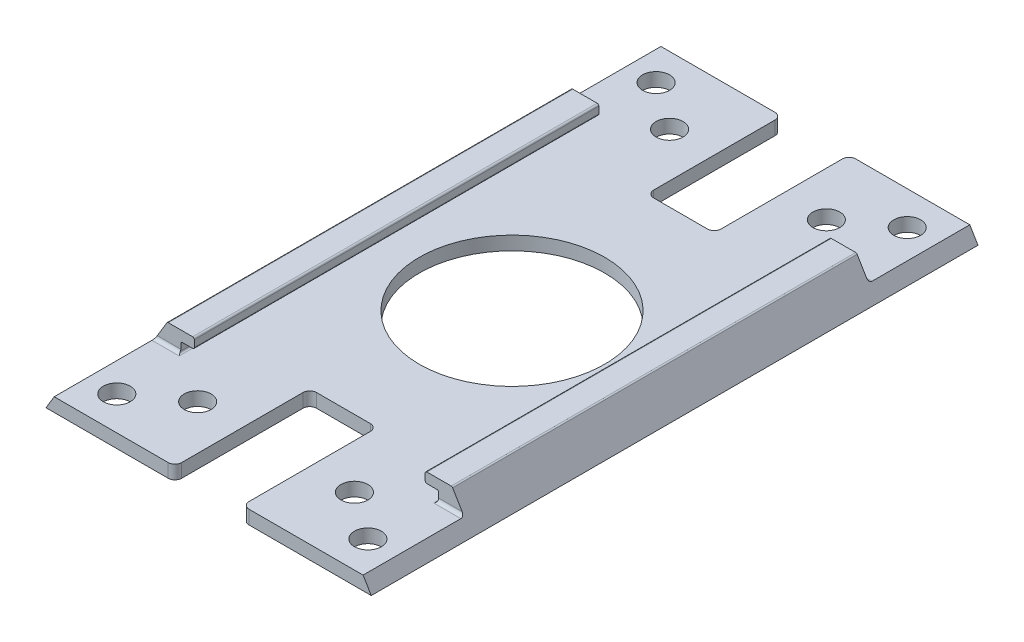
SolidWorks part; units mm, degrees
ref_plane "Front Plane" through (0, 0, 0) normal (0, 0, 1) x (1, 0, 0)
ref_plane "Top Plane" through (0, 0, 0) normal (0, 1, 0) x (1, 0, 0)
ref_plane "Right Plane" through (0, 0, 0) normal (1, 0, 0) x (0, 0, -1)
sketch "Sketch1" plane through (0, 0, 0) normal (0, 0, 1) x (1, 0, 0)
  line L0 (-79.85, -4.05) -> (3.65, -4.05)
  line L1 (0, 0) -> (-76.2, 0) construction
  line L2 (-76.2, 0) -> (-76.2, 2.8) construction
  line L3 (-76.35, 2.45) -> (-76.35, 0.5)
  line L4 (-76.2, 2.8) -> (-76.35, 2.8) construction
  line L5 (-76.2, 2.8) -> (-76.2, 2.95) construction
  line L6 (-76.2, 2.95) -> (-76.35, 2.95) construction
  line L7 (-76.35, 2.8) -> (-76.35, 2.95) construction
  line L8 (-75.85, 2.95) -> (-72.85, 2.95)
  line L9 (-72.35, 3.45) -> (-72.35, 5.45)
  line L10 (-72.85, 5.95) -> (-79.85, 5.95)
  line L13 (-38.1, -9.7056) -> (-38.1, 9.7056) construction
  line L16 (-79.85, 5.95) -> (-80.0669, 5.95)
  line L17 (-80.35, 5.95) -> (-80.35, -4.05) construction
  line L18 (-80.35, -4.05) -> (-86.35, -4.05)
  line L19 (-86.35, -4.05) -> (-80.4957, 5.7072)
  line L20 (-79.85, -4.05) -> (-80.35, -4.05)
  line L21 (-0.35, 0) -> (-75.85, 0)
  line L26 (4.15, 5.95) -> (4.15, -4.05) construction
  line L35 (0.15, 2.8) -> (0.15, 2.95) construction
  line L36 (0, 2.95) -> (0.15, 2.95) construction
  line L37 (0, 2.8) -> (0, 2.95) construction
  line L38 (0, 2.8) -> (0.15, 2.8) construction
  line L39 (0, 0) -> (0, 2.8) construction
  line L40 (3.65, -4.05) -> (4.15, -4.05)
  line L41 (10.15, -4.05) -> (4.2957, 5.7072)
  line L42 (4.15, -4.05) -> (10.15, -4.05)
  line L43 (3.65, 5.95) -> (3.8669, 5.95)
  line L44 (-3.35, 5.95) -> (3.65, 5.95)
  line L45 (-3.85, 3.45) -> (-3.85, 5.45)
  line L46 (-0.35, 2.95) -> (-3.35, 2.95)
  line L47 (0.15, 2.45) -> (0.15, 0.5)
  arc A0 (-72.35, 5.45) -> (-72.85, 5.95) centre (-72.85, 5.45) ccw
  arc A2 (-72.85, 2.95) -> (-72.35, 3.45) centre (-72.85, 3.45) ccw
  arc A4 (-76.35, 2.45) -> (-75.85, 2.95) centre (-75.85, 2.45) cw
  arc A5 (-76.35, 0.5) -> (-75.85, 0) centre (-75.85, 0.5) ccw
  arc A6 (-80.0669, 5.95) -> (-80.4957, 5.7072) centre (-80.0669, 5.45) ccw
  arc A12 (3.8669, 5.95) -> (4.2957, 5.7072) centre (3.8669, 5.45) cw
  arc A13 (0.15, 0.5) -> (-0.35, 0) centre (-0.35, 0.5) cw
  arc A14 (0.15, 2.45) -> (-0.35, 2.95) centre (-0.35, 2.45) ccw
  arc A15 (-3.35, 2.95) -> (-3.85, 3.45) centre (-3.35, 3.45) cw
  arc A16 (-3.85, 5.45) -> (-3.35, 5.95) centre (-3.35, 5.45) cw
  point P16 (-38.1, 0)
  point P21 (-72.35, 5.95)
  point P24 (-80.35, -4.05)
  point P27 (-72.35, 2.95)
  point P30 (-80.35, 5.95)
  point P60 (4.15, 5.95)
  point P61 (-3.85, 2.95)
  point P62 (4.15, -4.05)
  point P63 (-3.85, 5.95)
  dimension "D10" = 0.5
  dimension "D11" = 6
  dimension "D12" = 0.5
  dimension "D13" = 0.5
  dimension "D14" = 0.5
  dimension "D1" = 76.2
  dimension "D2" = 2.8
  dimension "D4" = 0.15
  dimension "D5" = 0.15
  dimension "D6" = 4
  dimension "D7" = 8
  dimension "D8" = 10
  dimension "D9" = 3
extrude "Boss-Extrude1" add sketch "Sketch1" along normal blind 180
sketch "Sketch2" plane through (0, 0, 180) normal (0, 0, 1) x (1, 0, 0)
  line L0 (-83.92, 0) -> (7.72, 0)
  line L1 (-86.35, -4.05) -> (-80.4957, 5.7072) construction
  line L2 (10.15, -4.05) -> (4.2957, 5.7072) construction
  line L3 (7.72, 0) -> (7.72, 8.017)
  line L4 (7.72, 8.017) -> (-83.92, 8.017)
  line L5 (-83.92, 8.017) -> (-83.92, 0)
  point P0 (7.72, 8.017)
  point P3 (-38.1, 0)
extrude "Cut-Extrude1" cut sketch "Sketch2" against normal blind 30
sketch "Sketch3" plane through (0, 0, 0) normal (0, 0, -1) x (-1, 0, 0)
  line L0 (83.92, 0) -> (-7.72, 0)
  line L1 (-7.72, 0) -> (-7.72, 8.4837)
  line L2 (-7.72, 8.4837) -> (83.92, 8.4837)
  line L3 (83.92, 8.4837) -> (83.92, 0)
  point P3 (38.1, 0)
  point P6 (0, 0)
  point P8 (0, 0)
  point P9 (0, 0)
  point P10 (0, 0)
  point P11 (-7.72, 0)
  point P13 (83.92, 0)
extrude "Cut-Extrude2" cut sketch "Sketch3" against normal blind 30
sketch "Sketch4" plane through (0, 0, 0) normal (0, 1, 0) x (1, 0, 0)
  line L0 (-178.1709, -90) -> (-35.3081, -90) construction
  line L1 (-38.1, -16.526) -> (-38.1, 16.526) construction
  line L2 (-86.35, 0) -> (-61.35, 0) construction
  line L4 (-61.35, 0) -> (-61.35, -20) construction
  line L5 (-61.35, -20) -> (-61.35, -10) construction
  line L6 (-61.35, -10) -> (-75.35, -10) construction
  line L7 (-14.85, 0) -> (-14.85, -20) construction
  line L8 (10.15, 0) -> (-14.85, 0) construction
  line L9 (-14.85, -10) -> (-0.85, -10) construction
  line L10 (-14.85, -20) -> (-14.85, -10) construction
  line L13 (-50.1, 0) -> (-86.35, 0)
  line L14 (-26.1, 0) -> (10.15, 0)
  line L15 (-50.1, 0) -> (-26.1, 0)
  line L16 (-14.85, -160) -> (-14.85, -170) construction
  line L17 (-14.85, -170) -> (-0.85, -170) construction
  line L18 (10.15, -180) -> (-14.85, -180) construction
  line L20 (10.15, -180) -> (10.15, 0) construction
  line L24 (-14.85, -180) -> (-14.85, -160) construction
  line L25 (-61.35, -170) -> (-75.35, -170) construction
  line L28 (-48.1, -2) -> (-48.1, -38)
  line L29 (-46.1, -40) -> (-30.1, -40)
  line L30 (-28.1, -38) -> (-28.1, -2)
  line L31 (-61.35, -160) -> (-61.35, -170) construction
  line L32 (-61.35, -180) -> (-61.35, -160) construction
  line L34 (-86.35, -180) -> (-61.35, -180) construction
  line L35 (-28.1, -142) -> (-28.1, -178)
  line L36 (-46.1, -140) -> (-30.1, -140)
  line L37 (-48.1, -178) -> (-48.1, -142)
  line L38 (-50.1, -180) -> (-26.1, -180)
  line L39 (-26.1, -180) -> (10.15, -180)
  line L40 (-50.1, -180) -> (-86.35, -180)
  line L41 (-86.35, -180) -> (-86.35, 0) construction
  circle A0 centre (-61.35, -20) radius 4
  circle A1 centre (-75.35, -10) radius 4
  circle A2 centre (-0.85, -10) radius 4
  circle A3 centre (-14.85, -20) radius 4
  circle A8 centre (-38.1, -90) radius 27.5
  arc A15 (-30.1, -40) -> (-28.1, -38) centre (-30.1, -38) ccw
  arc A16 (-48.1, -38) -> (-46.1, -40) centre (-46.1, -38) ccw
  arc A17 (-48.1, -2) -> (-50.1, 0) centre (-50.1, -2) ccw
  arc A18 (-28.1, -2) -> (-26.1, 0) centre (-26.1, -2) cw
  arc A19 (-28.1, -178) -> (-26.1, -180) centre (-26.1, -178) ccw
  arc A20 (-48.1, -178) -> (-50.1, -180) centre (-50.1, -178) cw
  arc A21 (-48.1, -142) -> (-46.1, -140) centre (-46.1, -142) cw
  arc A22 (-30.1, -140) -> (-28.1, -142) centre (-30.1, -142) cw
  circle A27 centre (-14.85, -160) radius 4
  circle A28 centre (-0.85, -170) radius 4
  circle A29 centre (-75.35, -170) radius 4
  circle A30 centre (-61.35, -160) radius 4
  point P3 (-38.1, -90)
  point P6 (-38.1, -90)
  point P27 (-38.1, 0)
  point P32 (-48.1, 0)
  point P36 (-28.1, 0)
  point P71 (-28.1, -180)
  point P72 (-48.1, -180)
  point P73 (-38.1, -180)
  point P74 (0, 0)
  point P75 (0, 0)
  point P76 (0, 0)
  point P77 (0, 0)
  point P78 (0, 0)
  point P79 (0, 0)
  dimension "D1" = 25
  dimension "D3" = 8
  dimension "D6" = 8
  dimension "D7" = 55
  dimension "D8" = 10
  dimension "D9" = 10
  dimension "D10" = 48.25
  dimension "D13" = 2
  dimension "D15" = 2
  dimension "D12" = 2
  dimension "D2" = 20
  dimension "D4" = 10
  dimension "D5" = 14
  dimension "D11" = 90
fillet "Fillet1" radius 1 1 edges at (-79.885, 0, 150)
fillet "Fillet2" radius 1 1 edges at (3.685, 0, 150)
fillet "Fillet3" radius 1 2 edges at (-79.885, 0, 30) (3.685, 0, 30)
extrude "Cut-Extrude3" cut sketch "Sketch4" against normal through all both contours L30 A18 L15 A17 L28 A16 L29 A15 | A1 | A0 | A3 | A2 | A8 | A22 L36 A21 L37 A20 L38 A19 L35 | A30 | A29 | A27 | A28
